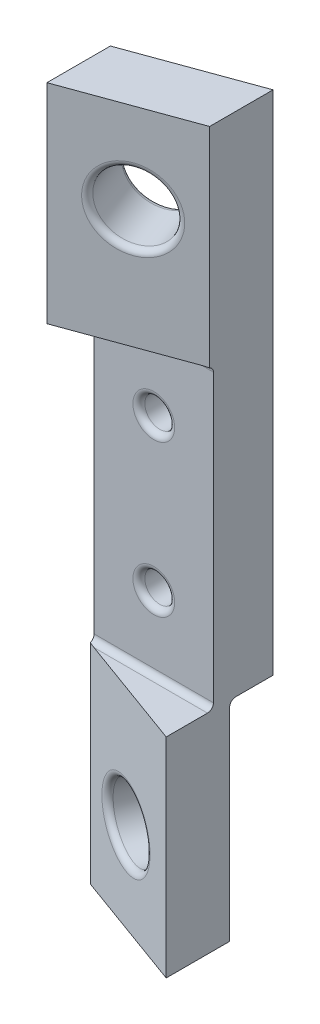
SolidWorks part; units mm, degrees
ref_plane "Front Plane" through (0, 0, 0) normal (1, 0, 0) x (0, 1, 0)
ref_plane "Top Plane" through (0, 0, 0) normal (0, 0, 1) x (0, 1, 0)
ref_plane "Right Plane" through (0, 0, 0) normal (0, 1, 0) x (-1, 0, 0)
sketch "Sketch1" plane through (0, 0, 0) normal (0, 0, 1) x (0, 1, 0)
  line L1 (-25, 10) -> (25, 10)
  line L2 (-25, 10) -> (-25, -10)
  line L3 (-25, -10) -> (25, -10)
  line L4 (25, 10) -> (25, -10)
  line L5 (-25, 10) -> (25, -10) construction
  line L6 (-25, -10) -> (25, 10) construction
  circle A0 centre (-12.7, 0) radius 2.5
  circle A1 centre (12.7, 0) radius 2.5
  point P0 (0, 0)
  dimension "D3" = 5
  dimension "D4" = 5
  dimension "D1" = 50
  dimension "D2" = 20
  dimension "D5" = 12.7
  dimension "D6" = 12.7
extrude "Boss-Extrude1" add sketch "Sketch1" along normal blind 10
sketch "Sketch3" plane through (0, -25, 0) normal (0, -1, 0) x (1, 0, 0)
  line L1 (10, 7.2794) -> (10, 17.9212)
  line L4 (10, 17.9212) -> (-10, 10.6418)
  line L8 (-10, 10) -> (-10, 0) construction
  line L10 (-10, 0) -> (10, 7.2794)
  line L11 (10, 10) -> (10, 0) construction
  line L13 (-10, 10.6418) -> (-10, 0)
  dimension "D1" = 10
extrude "Boss-Extrude2" add sketch "Sketch3" along normal blind 35
sketch "Sketch4" plane through (-4.59, 0, 12.6109) normal (-0.342, 0, 0.9397) x (0.9397, 0, 0.342)
  line L0 (15.5263, -60) -> (-5.7572, -60) construction
  line L1 (-5.7572, -60) -> (-5.7572, -25) construction
  circle A0 centre (4.2428, -45) radius 5.75
  dimension "D1" = 11.5
  dimension "D2" = 15
  dimension "D3" = 10
extrude "Cut-Extrude1" cut sketch "Sketch4" against normal blind 35
sketch "Sketch5" plane through (0, 25, 0) normal (0, 1, 0) x (-1, 0, 0)
  line L0 (-10, 0) -> (10, 7.2794)
  line L1 (10, 10) -> (10, 0) construction
  line L2 (10, 7.2794) -> (10, 17.9212)
  line L3 (10, 17.9212) -> (-10, 10.6418)
  line L4 (-10, 10) -> (-10, 0) construction
  line L5 (-10, 10.6418) -> (-10, 0)
  dimension "D1" = 10
extrude "Boss-Extrude3" add sketch "Sketch5" along normal blind 35
sketch "Sketch6" plane through (4.59, 0, 12.6109) normal (0.342, 0, 0.9397) x (0.9397, 0, -0.342)
  line L0 (-15.5263, 60) -> (5.7572, 60) construction
  line L1 (5.7572, 60) -> (5.7572, 25) construction
  circle A0 centre (-4.2428, 45) radius 5.75
  dimension "D1" = 11.5
  dimension "D2" = 15
  dimension "D3" = 10
extrude "Cut-Extrude2" cut sketch "Sketch6" against normal blind 35
fillet "Fillet1" radius 1 1 edges at (2.5, 12.7, 0)
fillet "Fillet2" radius 1 1 edges at (0, 25, 10)
fillet "Fillet3" radius 1 1 edges at (0, -25, 3.6397)
fillet "Fillet4" radius 1 1 edges at (0, -25, 10)
fillet "Fillet5" radius 1 1 edges at (0, 25, 3.6397)
fillet "Fillet6" radius 1 1 edges at (2.5861, 45, 2.6984)
fillet "Fillet7" radius 1 1 edges at (6.0063, 45, 12.0954)
fillet "Fillet8" radius 1 1 edges at (8.2204, -45, 6.6317)
fillet "Fillet9" radius 1 1 edges at (4.8002, -45, 16.0286)
fillet "Fillet10" radius 1 1 edges at (2.5, -12.7, 0)
fillet "Fillet11" radius 1 1 edges at (2.5, 12.7, 10)
fillet "Fillet12" radius 1 1 edges at (2.5, -12.7, 10)
